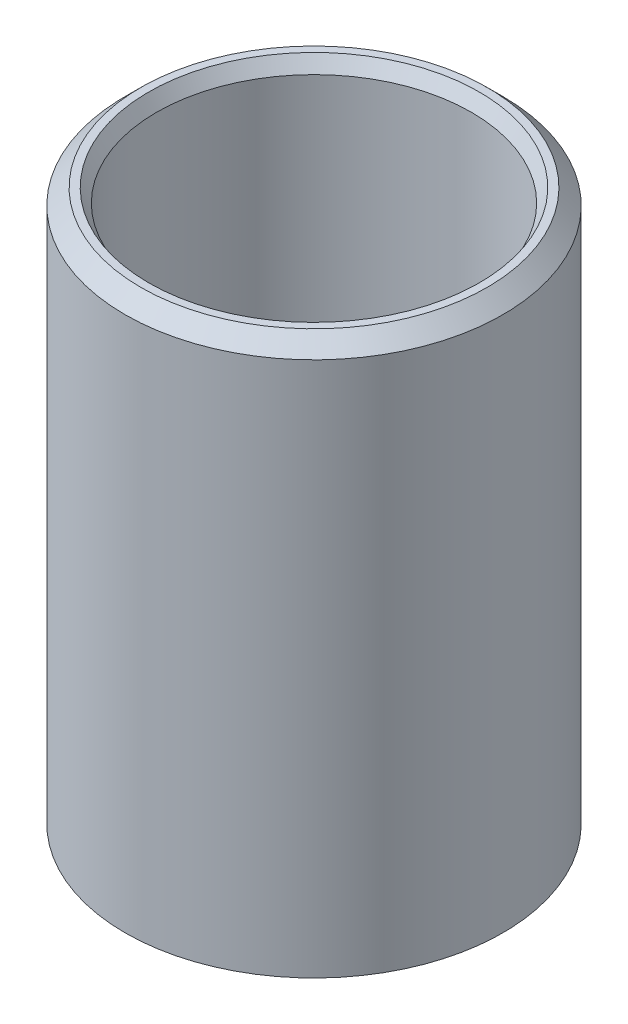
SolidWorks part; units mm, degrees
ref_plane "Front Plane" through (0, 0, 0) normal (0, 0, 1) x (1, 0, 0)
ref_plane "Top Plane" through (0, 0, 0) normal (0, 1, 0) x (1, 0, 0)
ref_plane "Right Plane" through (0, 0, 0) normal (1, 0, 0) x (0, 0, -1)
sketch "Sketch2" plane through (0, 0, 0) normal (0, 1, 0) x (1, 0, 0)
  circle A0 centre (0, 0) radius 30.48
  dimension "D1" = 60.96
extrude "Boss-Extrude2" add sketch "Sketch2" along normal blind 12.7
sketch "Sketch3" plane through (0, 12.7, 0) normal (0, 1, 0) x (1, 0, 0)
  line L0 (0, 15.24) -> (0, -15.24)
  circle A0 centre (0, 15.24) radius 4.125
  circle A1 centre (0, -15.24) radius 4.125
  point P5 (0, 0)
  dimension "D2" = 8.25
  dimension "D3" = 8.25
  dimension "D1" = 30.48
extrude "Cut-Extrude1" cut sketch "Sketch3" against normal blind 5.08
sketch "Sketch4" plane through (0, 7.62, 0) normal (0, 1, 0) x (1, 0, 0)
  circle A0 centre (0, 15.24) radius 2
  circle A1 centre (0, -15.24) radius 2
  dimension "D1" = 4
  dimension "D2" = 4
extrude "Cut-Extrude2" cut sketch "Sketch4" against normal through all
sketch "Sketch5" plane through (0, 12.7, 0) normal (0, 1, 0) x (1, 0, 0)
  circle A0 centre (0, 0) radius 30.48
  circle A1 centre (0, 0) radius 25.4
  dimension "D1" = 5.08
extrude "Boss-Extrude3" add sketch "Sketch5" along normal blind 76.2
chamfer "Chamfer1" distance 1.27 angle 60 1 edges at (0, 88.9, 25.4)
chamfer "Chamfer2" distance 2.54 angle 45 1 edges at (0, 88.9, 30.48)
chamfer "Chamfer3" distance 0.635 angle 30 2 edges at (0, 0, -13.24) (0, 0, 17.24)
